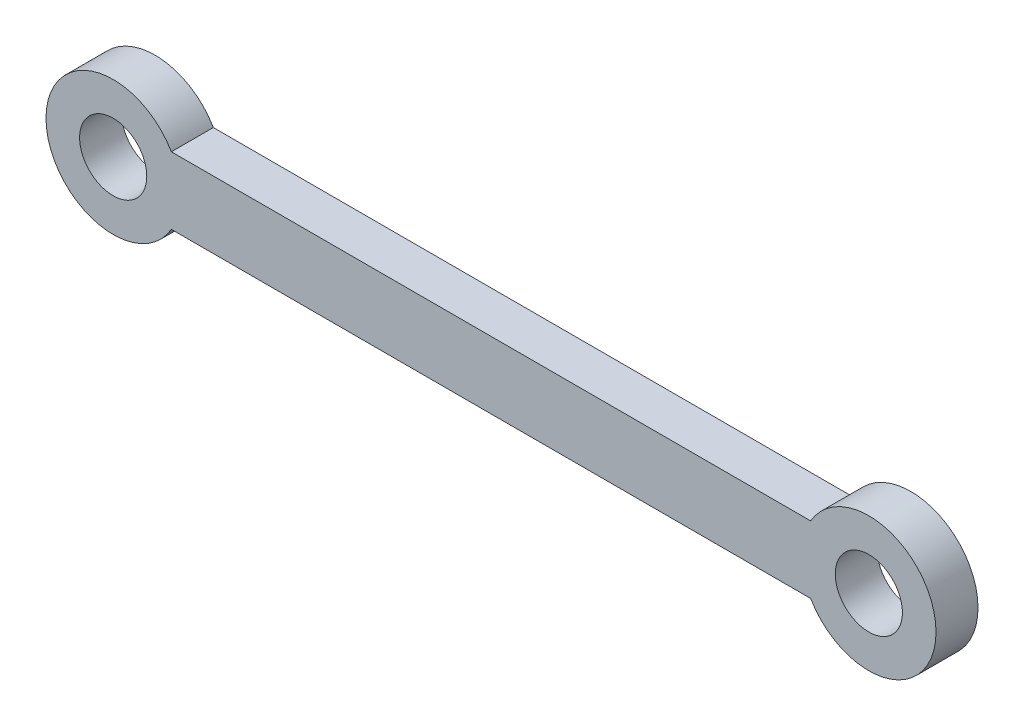
SolidWorks part; units mm, degrees
material "Acrylic (Medium-high impact)"
ref_plane "Front Plane" through (0, 0, 0) normal (0, 0, 1) x (1, 0, 0)
ref_plane "Top Plane" through (0, 0, 0) normal (0, 1, 0) x (1, 0, 0)
ref_plane "Right Plane" through (0, 0, 0) normal (1, 0, 0) x (0, 0, -1)
sketch "Sketch1" plane through (0, 0, 0) normal (0, 0, 1) x (1, 0, 0)
  line L0 (0, 2.54) -> (57.15, 2.54) construction
  line L1 (0, 0) -> (57.15, 0)
  line L2 (0, 0) -> (0, 5.08)
  line L3 (0, 5.08) -> (57.15, 5.08)
  line L4 (57.15, 0) -> (57.15, 5.08)
  line L5 (28.575, 5.08) -> (28.575, 0) construction
  circle A0 centre (0, 2.54) radius 5.08
  circle A1 centre (57.15, 2.54) radius 5.08
  dimension "D3" = 10.16
  dimension "D4" = 10.16
  dimension "D1" = 57.15
  dimension "D2" = 5.08
extrude "Boss-Extrude1" add sketch "Sketch1" along normal blind 3.175 contours L3 A0 L1 L2 | L1 A0 L3 L2 | A1 L3 A0 L1 | L3 A1 L1 L4 | L1 A1 L3 L4
sketch "Sketch2" plane through (0, 0, 3.175) normal (0, 0, 1) x (1, 0, 0)
  line L0 (-5.08, 2.54) -> (62.23, 2.54) construction
  line L1 (0, 7.62) -> (0, -2.54) construction
  line L2 (57.15, 7.62) -> (57.15, -2.54) construction
  arc A0 (4.3994, 5.08) -> (4.3994, 0) centre (0, 2.54) ccw construction
  arc A1 (52.7506, 0) -> (52.7506, 5.08) centre (57.15, 2.54) ccw construction
  circle A2 centre (0, 2.54) radius 2.54
  circle A4 centre (57.15, 2.54) radius 2.54
  dimension "D1" = 5.08
  dimension "D2" = 5.08
extrude "Cut-Extrude1" cut sketch "Sketch2" against normal through all
equation "\"hole-size\"=0.2"
equation "\"D1@Sketch2\"=\"hole-size\""
equation "\"D2@Sketch2\"=\"hole-size\""
